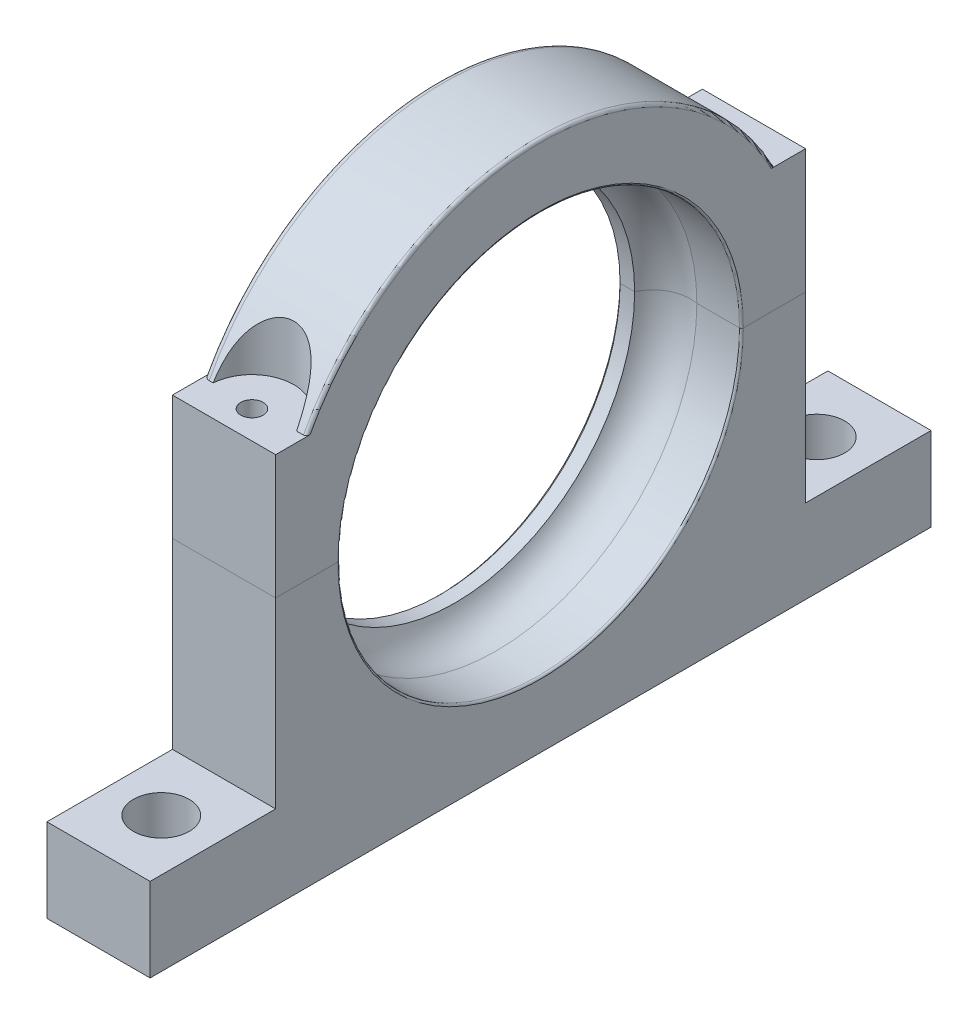
SolidWorks part; units mm, degrees
ref_plane "Plan de face" through (0, 0, 0) normal (0, 0, 1) x (1, 0, 0)
ref_plane "Plan de dessus" through (0, 0, 0) normal (0, 1, 0) x (1, 0, 0)
ref_plane "Plan de droite" through (0, 0, 0) normal (1, 0, 0) x (0, 0, -1)
sketch "Esquisse1" plane through (0, 0, 0) normal (0, 0, 1) x (1, 0, 0)
  line L0 (0, 92.9) -> (0, 65.5)
  line L1 (0, 65.5) -> (1.05, 64.45)
  line L2 (1.05, 64.45) -> (6.269, 64.45)
  line L3 (21.0021, 72.01) -> (36.3, 72.01)
  line L4 (37, 72.71) -> (37, 93.9)
  line L5 (35.9, 95) -> (2.1, 95)
  line L6 (-0.0013, 0) -> (37.0013, 0) construction
  arc A0 (2.1, 95) -> (0, 92.9) centre (2.1, 92.9) ccw
  arc A1 (6.269, 64.45) -> (21.0021, 72.01) centre (18.5, 58.75) cw
  arc A2 (36.3, 72.01) -> (37, 72.71) centre (36.3, 72.71) ccw
  arc A3 (37, 93.9) -> (35.9, 95) centre (35.9, 93.9) ccw
  dimension "D1" = 27.4
  dimension "D2" = 33.8
  dimension "D4" = 1.4849
  dimension "D8" = 1.5556
  dimension "D9" = 2.9699
revolve "Révolution1" add sketch "Esquisse1" angle 360 about L6
sketch "Esquisse2" plane through (0, 0, 0) normal (-1, 0, 0) x (0, 0, 1)
  line L0 (0, 0) -> (-116.9324, 0) construction
  line L1 (0, 0) -> (92.9, 0) construction
  line L2 (0, 0) -> (0, -89.4816) construction
  line L3 (14.4797, -95.5) -> (-102.4526, -95.5) construction
  line L4 (14.4797, -95.5) -> (138.829, -95.5) construction
  line L5 (0, -65.5) -> (155.3397, -65.5) construction
  line L6 (0, -65.5) -> (-123.2378, -65.5) construction
  line L8 (-95, -65.5) -> (-140, -65.5)
  line L9 (-140, -65.5) -> (-140, -95.5)
  line L10 (-140, -95.5) -> (140, -95.5)
  line L11 (140, -95.5) -> (140, -65.5)
  line L13 (95, -65.5) -> (140, -65.5)
  line L16 (-95, -65.5) -> (-95, 44.5)
  line L17 (-95, 44.5) -> (-81.5485, 44.5)
  line L18 (95, -65.5) -> (95, 44.5)
  line L19 (95, 44.5) -> (81.5485, 44.5)
  line L20 (92.9, 0) -> (95, 0) construction
  line L21 (95, 0) -> (112.4949, 0) construction
  circle A1 centre (0, 0) radius 65.5 construction
  circle A2 centre (0, 0) radius 92.9 construction
  arc A3 (-92.9, 0) -> (92.9, 0) centre (0, 0) ccw
  circle A5 centre (0, 0) radius 95 construction
  arc A6 (-81.5485, 44.5) -> (81.5485, 44.5) centre (0, 0) ccw
  circle M12 centre (0, 0) radius 92.9
  dimension "D1" = 45
  dimension "D2" = 30
  dimension "D3" = 110
extrude "Boss.-Extru.2" add sketch "Esquisse2" against normal blind 37 contours L18 L19 L17 L16 L8 L9 L10 L11 L13 M12
sketch "Esquisse4" plane through (0, 44.5, 0) normal (0, 1, 0) x (1, 0, 0)
  line L0 (37, 85) -> (0, 85) construction
  line L1 (37, 95) -> (37, 82.6859) construction
  line L2 (0, 95) -> (0, 81.5485) construction
  line L3 (37, 95) -> (0, 95) construction
  circle A0 centre (18.5, 85) radius 15
  point P10 (18.5, 95)
  dimension "D1" = 30
  dimension "D2" = 10
extrude "Enlèv. mat.-Extru.1" cut sketch "Esquisse4" along normal blind 37 contours A0
sketch "Esquisse6" plane through (0, 44.5, 0) normal (0, 1, 0) x (1, 0, 0)
  line L0 (37, 95) -> (0, 95) construction
  line L1 (0, 95) -> (0, 81.5485) construction
  circle A0 centre (18.5, 85) radius 4
  dimension "D2" = 8
  dimension "D1" = 10
  dimension "D3" = 18.5
extrude "Enlèv. mat.-Extru.2" cut sketch "Esquisse6" against normal blind 100
sketch "Esquisse7" plane through (0, -65.5, 0) normal (0, 1, 0) x (1, 0, 0)
  line L0 (0, 117.5) -> (37, 117.5) construction
  line L3 (18.5, 140) -> (18.5, 95) construction
  line L4 (37, 140) -> (0, 140) construction
  line L5 (37, 95) -> (0, 95) construction
  line L6 (0, 95) -> (0, 140) construction
  line L7 (37, 95) -> (37, 140) construction
  circle A0 centre (18.5, 117.5) radius 10
  dimension "D1" = 20
extrude "Enlèv. mat.-Extru.3" cut sketch "Esquisse7" against normal through all
mirror "Symétrie1" about plane through (0, 0, 0) normal (0, 0, 1) of "Enlèv. mat.-Extru.3", "Enlèv. mat.-Extru.2", "Enlèv. mat.-Extru.1"
sketch "Esquisse8" plane through (37, 0, 0) normal (1, 0, 0) x (0, 0, -1)
  line L0 (-95, 0) -> (95, 0)
  line L1 (-95, -65.5) -> (-95, 44.5) construction
  line L2 (95, -65.5) -> (95, 44.5) construction
split "Fractionner2" trim tools "Esquisse8" bodies to split 110 resulting bodies 112 113
